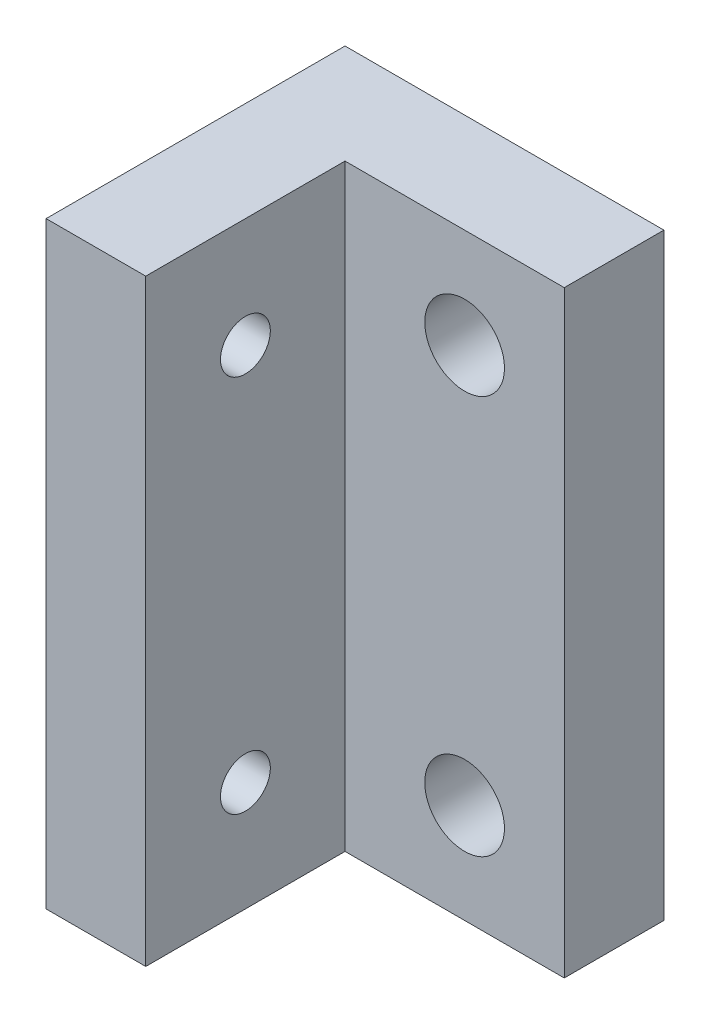
SolidWorks part; units mm, degrees
ref_plane "Front Plane" through (0, 0, 0) normal (0, 0, 1) x (1, 0, 0)
ref_plane "Top Plane" through (0, 0, 0) normal (0, 1, 0) x (1, 0, 0)
ref_plane "Right Plane" through (0, 0, 0) normal (1, 0, 0) x (0, 0, -1)
sketch "Sketch1" plane through (0, 0, 0) normal (0, 1, 0) x (1, 0, 0)
  line L1 (0, 0) -> (16, 0)
  line L2 (0, 0) -> (0, -15)
  line L3 (0, -15) -> (5, -15)
  line L4 (16, 0) -> (16, -5)
  line L7 (16, -5) -> (5, -5)
  line L8 (5, -15) -> (5, -5)
  dimension "D1" = 15
  dimension "D2" = 16
  dimension "D3" = 5
  dimension "D4" = 5
extrude "Boss-Extrude1" add sketch "Sketch1" along normal mid plane 30
sketch "Sketch2" plane through (0, 0, 5) normal (0, 0, 1) x (1, 0, 0)
  line L0 (11, 10) -> (11, -10) construction
  line L1 (11, 0) -> (16, 0) construction
  line L2 (16, 15) -> (16, -15) construction
  circle A0 centre (11, 10) radius 2
  circle A1 centre (11, -10) radius 2
  dimension "D2" = 4
  dimension "D1" = 5
  dimension "D3" = 20
extrude "Cut-Extrude1" cut sketch "Sketch2" against normal through all
sketch "Sketch3" plane through (0, 0, 0) normal (-1, 0, 0) x (0, 0, 1)
  line L0 (10, -9.5) -> (10, 9.5) construction
  line L1 (15, 15) -> (15, -15) construction
  line L2 (10, 0) -> (15, 0) construction
  circle A0 centre (10, 9.5) radius 1.25
  circle A1 centre (10, -9.5) radius 1.25
  dimension "D3" = 2.5
  dimension "D1" = 19
  dimension "D2" = 5
extrude "Cut-Extrude2" cut sketch "Sketch3" against normal through all
